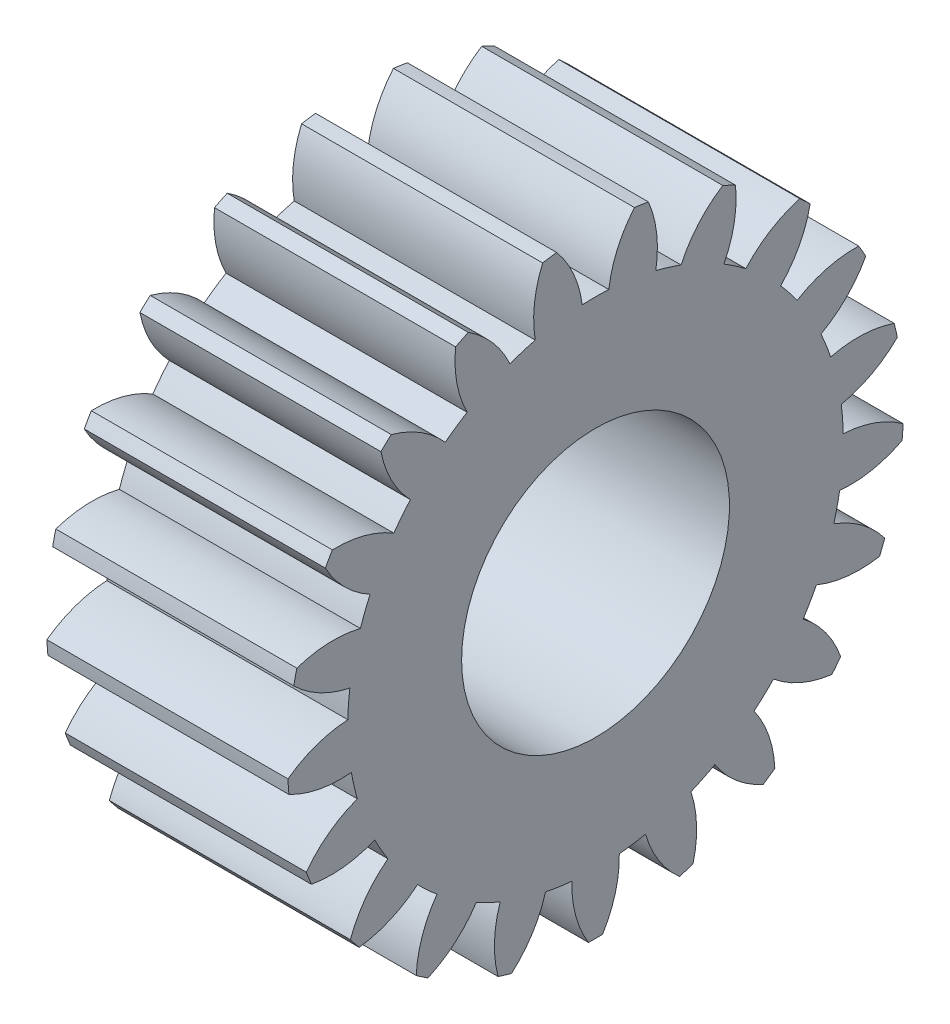
SolidWorks part; units mm, degrees
ref_plane "Plane1" through (0, 0, 0) normal (0, 0, 1) x (1, 0, 0)
ref_plane "Plane2" through (0, 0, 0) normal (0, 1, 0) x (1, 0, 0)
ref_plane "Plane3" through (0, 0, 0) normal (1, 0, 0) x (0, 0, -1)
other "Configuration Table"
sketch "HoldingSke" plane through (0, 0, 0) normal (0, 1, 0) x (1, 0, 0)
  line L0 (0, 0) -> (0.9336, -0.3584)
  line L1 (-15, 0) -> (100, 0) construction
  line L2 (0, 0) -> (-2.1039, 2.3779)
  line L3 (0, 0) -> (-11.863, 4.5341)
  line L4 (0, 0) -> (8.0624, 3.0949)
  line L5 (0, 0) -> (-46.8476, -17.4728)
  line L6 (0, 0) -> (-7.4607, -5.0337)
  line L7 (-2.1039, 2.3779) -> (8.6586, 51.2059)
  line L8 (-76.2, 54.61) -> (-74.4, 54.61)
  line L9 (-71.009, 38.7566) -> (-53.1078, 45.2721)
  line L10 (-76.2, 71.12) -> (104.1128, 71.12)
  line L11 (0, 0) -> (-9, 0)
  line L12 (-76.2, 101.6) -> (-76.162, 101.6)
  line L13 (24.9733, 27.94) -> (52.9518, 28.4284)
  line L14 (24.9733, 27.94) -> (24.9743, 27.94)
  line L15 (24.9733, 27.94) -> (100.4006, 29.5858)
  line L16 (-63.627, -1) -> (-12.827, -1)
  circle A0 centre (0, 0) radius 5
  circle A1 centre (0, 0) radius 9.249
  circle A2 centre (0, 0) radius 37.5
  circle A3 centre (0, 0) radius 5
  dimension "MHD" = 18.498
  dimension "Hub_dia" = 75
  dimension "Bore" = 10
  dimension "MBD" = 10
  dimension "Num_teeth" = 21
  dimension "Pitch" = 1
  dimension "Overall_len" = 50
  dimension "Show_teeth" = 21
  dimension "Thickness" = 9
  dimension "OAL" = 50.0001
  dimension "T_dim" = 1.8
  dimension "Ap" = 20
  dimension "H" = 19.05
  dimension "Pitch_radius" = 180.3128
  dimension "Width" = 9
  dimension "Backlash" = 0.038
  dimension "Addendum_fac" = 1
  dimension "Dedendum_fac" = 1.25
  dimension "Clearance_fac" = 0.25
  dimension "Dedendum_add" = 0.001
  dimension "Module" = 1
sketch "BasProSke" plane through (0, 0, 0) normal (0, 1, 0) x (1, 0, 0)
  line L0 (-10, 0) -> (60, 0) construction
  line L1 (0, 0) -> (0, 11.5)
  line L2 (0, 0) -> (9, 0)
  line L3 (9, 0) -> (9, 11.5)
  line L4 (9, 11.5) -> (0, 11.5)
  dimension "Thickness" = 9
  dimension "Diameter" = 23
revolve "Base-Revolve" add sketch "BasProSke" angle 360 about L0
sketch "TooCutSke" plane through (0, 0, 0) normal (1, 0, 0) x (0, 0, -1)
  line L1 (0, 0) -> (0, 107) construction
  line L2 (0, 0) -> (-0.8511, 10.4654) construction
  line L3 (0, 0) -> (-3.1226, 20.7168) construction
  line L4 (-0.8511, 10.4654) -> (-1.5613, 10.3584) construction
  arc A0 (0.4953, 9.2357) -> (-0.4953, 9.2357) centre (0, 0) ccw
  arc A1 (1.4725, 11.431) -> (-1.4725, 11.431) centre (0, 0) ccw
  circle A2 centre (0, 0) radius 10.5 construction
  circle A3 centre (0, 0) radius 9.8668 construction
  arc A4 (-0.4953, 9.2357) -> (-1.4725, 11.431) centre (-4.6605, 8.6967) ccw
  arc A5 (1.4725, 11.431) -> (0.4953, 9.2357) centre (4.6605, 8.6967) ccw
  dimension "Root_dia" = 18.498
  dimension "Overcut_dia" = 23.0508
  dimension "Pitch_dia" = 21
  dimension "Base_dia" = 19.7335
  dimension "Flank_rad" = 4.2
  dimension "Half_ang" = 8.571
  dimension "Half_CT" = 0.7182
extrude "ToothCut" cut sketch "TooCutSke" along normal through all
fillet "Breaks" [suppressed] radius 0.02
fillet "RootFillets" [suppressed] radius 0.251
pattern_circular "TeethCuts" count 21 every 17.143 about axis through (-10, 0, 0) along (1, 0, 0) of "ToothCut", "RootFillets", "Breaks"
sketch "HubNeaOneSke" plane through (0, 0, 0) normal (-1, 0, 0) x (0, 0, 1)
  circle A0 centre (0, 0) radius 9.249
  dimension "Diameter" = 18.498
extrude "HubNearOne" [suppressed] add sketch "HubNeaOneSke" along normal blind 41.0001
sketch "HubNeaBotSke" plane through (0, 0, 0) normal (-1, 0, 0) x (0, 0, 1)
  circle A0 centre (0, 0) radius 9.249
  dimension "Diameter" = 18.498
extrude "HubNearBoth" [suppressed] add sketch "HubNeaBotSke" along normal blind 20.5
ref_plane "FarPln" through (9, 0, 0) normal (1, 0, 0) x (0, 0, -1)
sketch "HubFarSke" plane through (9, 0, 0) normal (1, 0, 0) x (0, 0, -1)
  circle A0 centre (0, 0) radius 9.249
  dimension "Diameter" = 18.498
extrude "HubFar" [suppressed] add sketch "HubFarSke" along normal blind 20.5
sketch "BorSke" plane through (0, 0, 0) normal (1, 0, 0) x (0, 0, -1)
  circle A0 centre (0, 0) radius 5
  dimension "Diameter" = 10
extrude "Bore" cut sketch "BorSke" along normal mid plane 100.0001
sketch "KeySke" plane through (0, 0, 0) normal (1, 0, 0) x (0, 0, -1)
  line L0 (-2, 0) -> (-2, 6.8)
  line L1 (-2, 6.8) -> (2, 6.8)
  line L2 (2, 6.8) -> (2, 0)
  line L3 (0, 0) -> (0, 34) construction
  line L4 (-2, 0) -> (2, 0)
  dimension "Offset" = 6.8
  dimension "Width" = 4
extrude "Keyway" [suppressed] cut sketch "KeySke" along normal mid plane 100.0001
pattern_circular "Keyway2" [suppressed] count 2 every 90 about axis through (-10, 0, 0) along (1, 0, 0)
equation "' \"Module@HoldingSke\" = 6.35"
equation "' \"Num_teeth@HoldingSke\" = 12"
equation "' \"Ap@HoldingSke\" =  20"
equation "' \"Ap@HoldingSke\" = 20"
equation "' \"Width@HoldingSke\" = 0.5 * 25.4"
equation "' \"Hub_dia@HoldingSke\"= 1 * 25.4"
equation "' \"Hub_dia@HoldingSke\" = 1 * 25.4"
equation "' \"Overall_len@HoldingSke\" = 1.0 * 25.4"
equation "' \"Bore@HoldingSke\" = 0.75 * 25.4"
equation "' \"T_dim@HoldingSke\" = 0.1 * 25.4"
equation "' \"Width@KeySke\" = 0.25 * 25.4"
equation "' \"Show_teeth@HoldingSke\" = 13"
equation "' \"Backlash@HoldingSke\" = 0.009 * 25.4"
equation "' \"Addendum_fac@HoldingSke\" = 1.0"
equation "' \"Dedendum_fac@HoldingSke\" = 1.25"
equation "' \"Dedendum_add@HoldingSke\" = 0.00005 * 25.4"
equation "' \"Clearance_fac@HoldingSke\" = 0.25"
equation "\"Pitch@HoldingSke\" = 1 / \"Module@HoldingSke\""
equation "\"Overcut_dia@TooCutSke\" = (\"Num_teeth@HoldingSke\" + 2 * \"Addendum_fac@HoldingSke\") / \"Pitch@HoldingSke\" + 0.002 * 25.4"
equation "\"Pitch_dia@TooCutSke\" = \"Num_teeth@HoldingSke\" / \"Pitch@HoldingSke\""
equation "\"Base_dia@TooCutSke\" = \"Num_teeth@HoldingSke\" / \"Pitch@HoldingSke\" * cos((\"Ap@HoldingSke\"  * 3.14159265 / 180))"
equation "\"Root_dia@TooCutSke\" = (\"Num_teeth@HoldingSke\" + 2) / \"Pitch@HoldingSke\" - 2 * (\"Addendum_fac@HoldingSke\" + \"Dedendum_fac@HoldingSke\") / \"Pitch@HoldingSke\" - \"Dedendum_add@HoldingSke\" * 2"
equation "\"Half_ang@TooCutSke\" = 180 / \"Num_teeth@HoldingSke\""
equation "\"Half_CT@TooCutSke\" = \"Num_teeth@HoldingSke\" / \"Pitch@HoldingSke\" * sin((3.14159265 / 2 / \"Num_teeth@HoldingSke\")) / 2 - 7 * \"Backlash@HoldingSke\" / 4"
equation "\"Flank_rad@TooCutSke\" = \"Num_teeth@HoldingSke\" / \"Pitch@HoldingSke\" / 5"
equation "\"Radius@RootFillets\" = \"Clearance_fac@HoldingSke\" / \"Pitch@HoldingSke\" + \"Dedendum_add@HoldingSke\""
equation "\"Break_rad@Breaks\" = 0.02 / \"Pitch@HoldingSke\""
equation "\"Thickness@HoldingSke\" = \"Width@HoldingSke\""
equation "\"OAL@HoldingSke\" = \"Thickness@HoldingSke\""
equation "\"MHD@HoldingSke\" = (\"Num_teeth@HoldingSke\" + 2) / \"Pitch@HoldingSke\" - 2 * (\"Addendum_fac@HoldingSke\" + \"Dedendum_fac@HoldingSke\")  / \"Pitch@HoldingSke\" - \"Dedendum_add@HoldingSke\" * 2"
equation "\"MBD@HoldingSke\" = (\"Num_teeth@HoldingSke\" + 2) / \"Pitch@HoldingSke\" - 2 * (\"Addendum_fac@HoldingSke\" + \"Dedendum_fac@HoldingSke\")  / \"Pitch@HoldingSke\" - \"Dedendum_add@HoldingSke\" * 2 - 0.002 * 25.4"
equation "\"MHD@HoldingSke\" = ((sgn( \"MHD@HoldingSke\" - \"Hub_dia@HoldingSke\" )-1)*( \"MHD@HoldingSke\" - \"Hub_dia@HoldingSke\" ))/-2+ \"Hub_dia@HoldingSke\""
equation "\"MBD@HoldingSke\" = ((sgn( \"MBD@HoldingSke\" - \"Bore@HoldingSke\" )-1)*( \"MBD@HoldingSke\" - \"Bore@HoldingSke\" ))/-2+ \"Bore@HoldingSke\""
equation "\"OAL@HoldingSke\" = ((sgn( \"OAL@HoldingSke\" - \"Overall_len@HoldingSke\" )+1)*( \"OAL@HoldingSke\" - \"Overall_len@HoldingSke\" ))/2 + \"Overall_len@HoldingSke\" + 0.000002 * 25.4"
equation "\"Num_teeth@TeethCuts\" = int( \"Show_teeth@HoldingSke\" ) + 1"
equation "\"Num_teeth@TeethCuts\" = ((sgn( \"Num_teeth@TeethCuts\" - \"Num_teeth@HoldingSke\" )-1)*( \"Num_teeth@TeethCuts\" - \"Num_teeth@HoldingSke\" ))/-2+ \"Num_teeth@HoldingSke\""
equation "\"Num_teeth@TeethCuts\" = ((sgn( \"Num_teeth@TeethCuts\" - 2.0)+1)*( \"Num_teeth@TeethCuts\" - 2.0))/2 +2.0"
equation "\"Angle@TeethCuts\" = 360.0 / \"Num_teeth@HoldingSke\""
equation "\"Diameter@BasProSke\" = (\"Num_teeth@HoldingSke\" + 2 * \"Addendum_fac@HoldingSke\") / \"Pitch@HoldingSke\""
equation "\"Thickness@BasProSke\"  = \"Thickness@HoldingSke\""
equation "' \"Fillet_rad@BasProSke\" =  \"Thickness@HoldingSke\" * 0.05"
equation "' \"Fillet_rad@BasProSke\" = \"Thickness@HoldingSke\" * 0.05"
equation "\"MHD@HoldingSke\" = ((sgn( \"MHD@HoldingSke\" - \"Root_dia@TooCutSke\" )-1)*( \"MHD@HoldingSke\" - \"Root_dia@TooCutSke\" ))/-2+ \"Root_dia@TooCutSke\""
equation "\"Diameter@HubNeaOneSke\" = \"MHD@HoldingSke\""
equation "\"Length@HubNearOne\" = \"OAL@HoldingSke\" - \"Thickness@BasProSke\""
equation "\"Diameter@HubNeaBotSke\" = \"MHD@HoldingSke\""
equation "\"Length@HubNearBoth\" = ( \"OAL@HoldingSke\" - \"Thickness@BasProSke\" ) / 2.0"
equation "\"Thickness@FarPln\" = \"Thickness@BasProSke\""
equation "\"Diameter@HubFarSke\" = \"MHD@HoldingSke\""
equation "\"Length@HubFar\" = ( \"OAL@HoldingSke\" - \"Thickness@BasProSke\" ) / 2.0"
equation "\"Diameter@BorSke\" = \"MBD@HoldingSke\""
equation "\"D1@Bore\" = \"OAL@HoldingSke\" * 2.0"
equation "\"D1@Keyway\" = \"OAL@HoldingSke\" * 2.0"
equation "\"Offset@KeySke\" = \"T_dim@HoldingSke\" + \"MBD@HoldingSke\" / 2.0"
